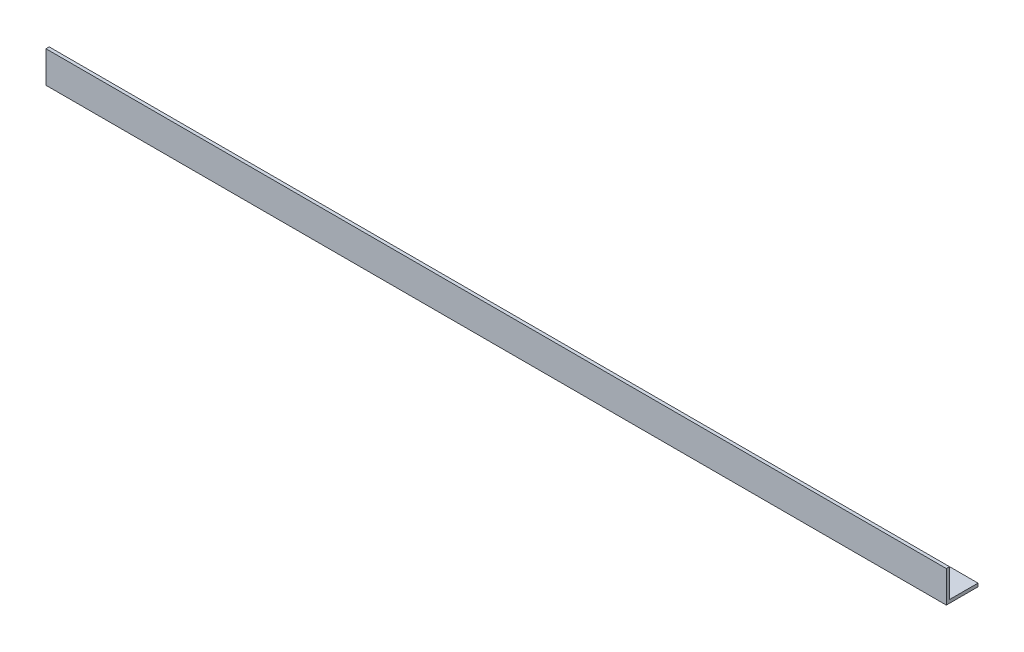
SolidWorks part; units mm, degrees
ref_plane "Alzado" through (0, 0, 0) normal (0, 0, 1) x (1, 0, 0)
ref_plane "Planta" through (0, 0, 0) normal (0, 1, 0) x (1, 0, 0)
ref_plane "Vista lateral" through (0, 0, 0) normal (1, 0, 0) x (0, 0, -1)
sketch "Croquis2" plane through (0, 0, 0) normal (1, 0, 0) x (0, 0, -1)
  line L0 (0, 0) -> (0, -12.7)
  line L1 (0, -12.7) -> (12.7, -12.7)
  line L2 (12.7, -12.7) -> (12.7, -11.4)
  line L3 (12.7, -11.4) -> (1.3, -11.4)
  line L4 (1.3, -11.4) -> (1.3, 0)
  line L5 (1.3, 0) -> (0, 0)
  dimension "D1" = 1.3
  dimension "D2" = 1.3
  dimension "D3" = 12.7
  dimension "D4" = 12.7
extrude "Saliente-Extruir1" add sketch "Croquis2" along normal blind 361
